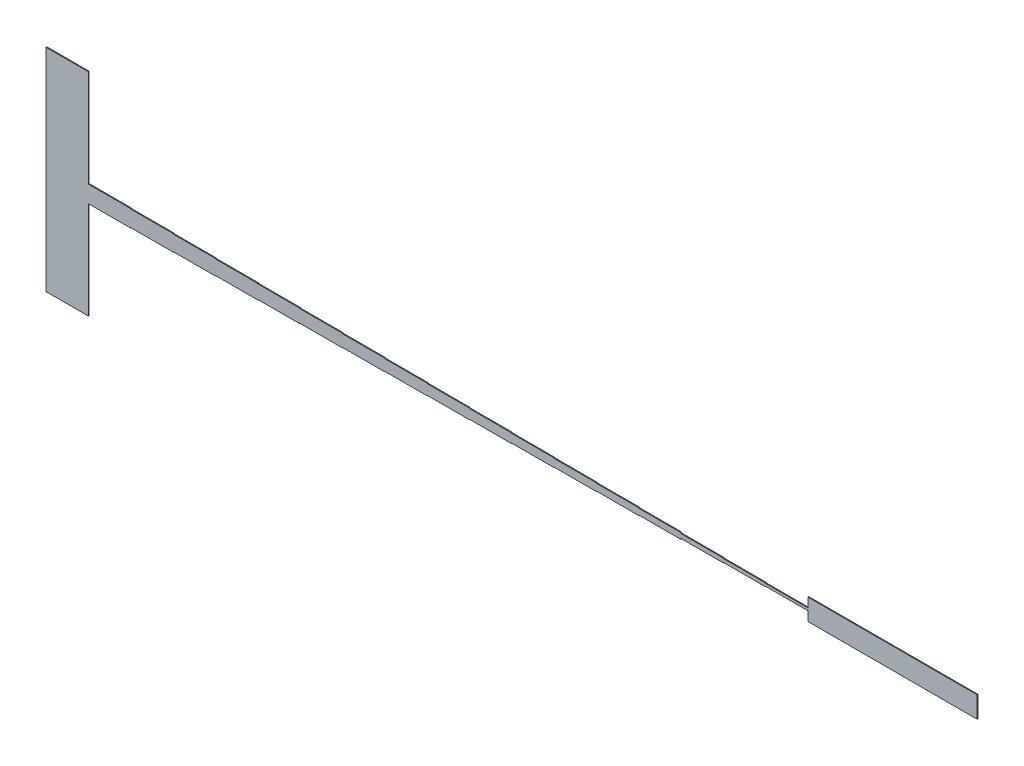
SolidWorks part; units mm, degrees
ref_plane "Front Plane" through (0, 0, 0) normal (0, 0, 1) x (1, 0, 0)
ref_plane "Top Plane" through (0, 0, 0) normal (0, 1, 0) x (1, 0, 0)
ref_plane "Right Plane" through (0, 0, 0) normal (1, 0, 0) x (0, 0, -1)
sketch "Sketch1" plane through (0, 0, 0) normal (0, 0, 1) x (1, 0, 0)
  line L0 (1000, 250) -> (41000, 250)
  line L1 (-1000, 2500) -> (1000, 2500)
  line L2 (-1000, 2500) -> (-1000, -2500)
  line L3 (-1000, -2500) -> (1000, -2500)
  line L4 (1000, 2500) -> (1000, 250)
  line L5 (-1000, 2500) -> (1000, -2500) construction
  line L6 (-1000, -2500) -> (1000, 2500) construction
  line L9 (1000, -250) -> (41000, -250)
  line L11 (33000, 250) -> (41000, -250) construction
  line L12 (33000, -250) -> (41000, 250) construction
  line L17 (1000, 125) -> (9000, -125) construction
  line L18 (1000, -125) -> (9000, 125) construction
  line L23 (6000, 100) -> (12000, -100) construction
  line L24 (6000, -100) -> (12000, 100) construction
  line L25 (1000, -250) -> (1000, -2500)
  line L29 (41000, 250) -> (41000, -250)
  point P0 (0, 0)
  point P6 (37000, 0)
  point P11 (5000, 0)
  point P16 (9000, 0)
  dimension "D1" = 2000
  dimension "D2" = 5000
  dimension "D3" = 500
  dimension "D4" = 40000
  dimension "D5" = 250
  dimension "D7" = 200
extrude "Boss-Extrude1" add sketch "Sketch1" against normal blind 20
sketch "Sketch2" plane through (0, 0, 0) normal (0, 0, 1) x (1, 0, 0)
  line L0 (0, -55) -> (0, 55) construction
  line L1 (1000, 2500) -> (0, 2500)
  line L2 (1000, 2500) -> (1000, 250)
  line L3 (1000, 250) -> (0, 250)
  line L4 (0, 2500) -> (0, 250)
  line L5 (1000, -2500) -> (0, -2500)
  line L6 (1000, -2500) -> (1000, -250)
  line L7 (1000, -250) -> (0, -250)
  line L8 (0, -2500) -> (0, -250)
  dimension "D1" = 1000
  dimension "D2" = 2250
extrude "Cut-Extrude1" cut sketch "Sketch2" against normal through all
sketch "Sketch3" plane through (0, 0, 0) normal (0, 0, 1) x (1, 0, 0)
  line L0 (0, 250) -> (0, 200)
  line L1 (0, 200) -> (1000, 200)
  line L2 (1000, 200) -> (1000, 190)
  line L3 (1000, 190) -> (2000, 190)
  line L4 (2000, 190) -> (2000, 180)
  line L5 (2000, 180) -> (3000, 180)
  line L6 (3000, 180) -> (3000, 170)
  line L7 (3000, 170) -> (4000, 170)
  line L8 (4000, 170) -> (4000, 160)
  line L9 (4000, 160) -> (5000, 160)
  line L10 (5000, 160) -> (5000, 150)
  line L11 (5000, 150) -> (6000, 150)
  line L12 (6000, 150) -> (6000, 140)
  line L13 (6000, 140) -> (7000, 140)
  line L14 (7000, 140) -> (7000, 130)
  line L15 (7000, 130) -> (8000, 130)
  line L16 (8000, 130) -> (8000, 120)
  line L17 (8000, 120) -> (9000, 120)
  line L18 (9000, 120) -> (9000, 110)
  line L19 (9000, 110) -> (10000, 110)
  line L20 (10000, 110) -> (10000, 100)
  line L21 (10000, 100) -> (11000, 100)
  line L22 (11000, 100) -> (11000, 90)
  line L23 (11000, 90) -> (12000, 90)
  line L24 (12000, 90) -> (12000, 80)
  line L25 (12000, 80) -> (13000, 80)
  line L26 (13000, 80) -> (13000, 70)
  line L27 (13000, 70) -> (14000, 70)
  line L28 (14000, 70) -> (14000, 50)
  line L29 (14000, 50) -> (15000, 50)
  line L30 (15000, 50) -> (15000, 40)
  line L32 (15000, 40) -> (16000, 40)
  line L33 (16000, 40) -> (16000, 30)
  line L34 (16000, 30) -> (17000, 30)
  line L35 (0, 250) -> (17000, 250)
  line L36 (41000, 250) -> (0, 250) construction
  line L37 (17000, 250) -> (17000, 30)
  dimension "D1" = 50
  dimension "D2" = 1000
  dimension "D3" = 10
  dimension "D4" = 1000
  dimension "D5" = 10
  dimension "D6" = 10
  dimension "D7" = 1000
  dimension "D8" = 1000
  dimension "D9" = 10
  dimension "D10" = 1000
  dimension "D11" = 10
  dimension "D12" = 1000
  dimension "D13" = 10
  dimension "D14" = 1000
  dimension "D15" = 10
  dimension "D16" = 1000
  dimension "D17" = 10
  dimension "D18" = 1000
  dimension "D19" = 10
  dimension "D20" = 1000
  dimension "D21" = 10
  dimension "D22" = 1000
  dimension "D23" = 10
extrude "Cut-Extrude3" cut sketch "Sketch3" against normal through all
mirror "Mirror1" about plane through (0, 0, 0) normal (0, 1, 0) of "Cut-Extrude3"
sketch "Sketch4" plane through (0, 0, 0) normal (0, 0, 1) x (1, 0, 0)
  line L0 (41000, 250) -> (17000, 250) construction
  line L1 (41000, -250) -> (21000, -250)
  line L2 (41000, -250) -> (41000, 250)
  line L3 (41000, 250) -> (21000, 250)
  line L4 (21000, -250) -> (21000, 250)
  line L5 (17000, -30) -> (17000, -250) construction
  dimension "D1" = 4000
extrude "Cut-Extrude4" cut sketch "Sketch4" against normal through all
